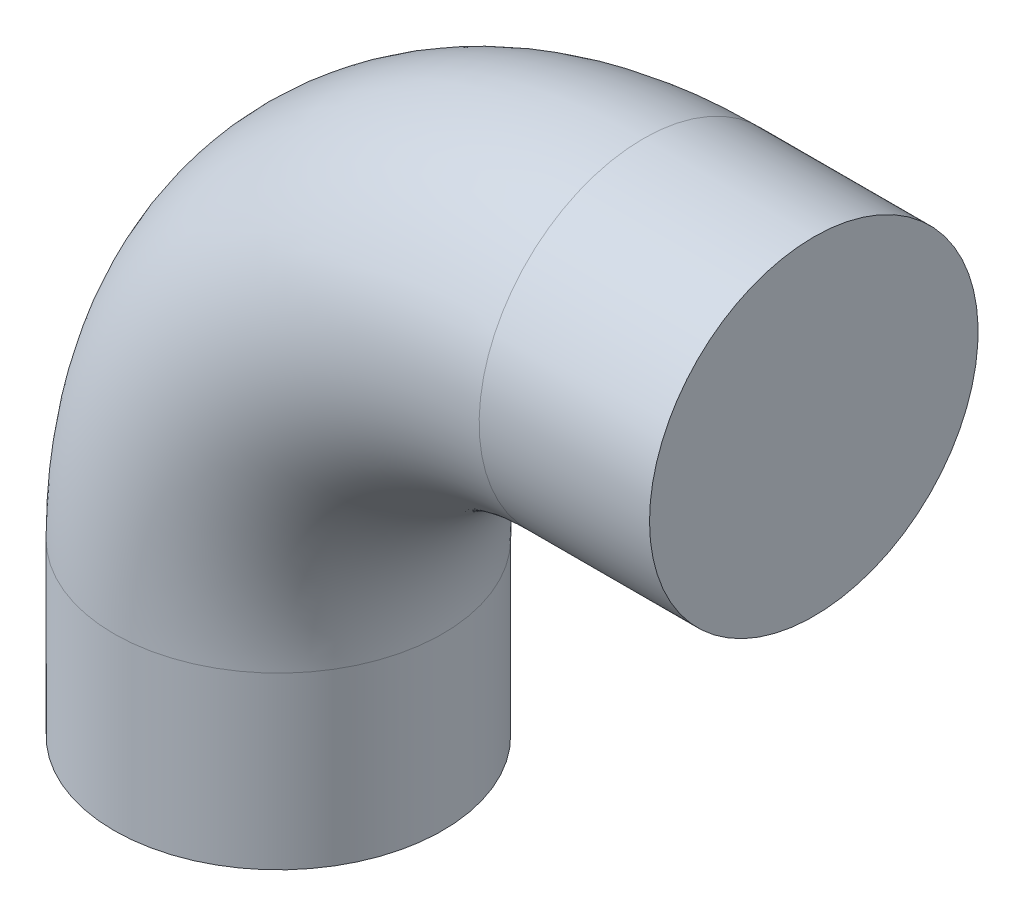
SolidWorks part; units mm, degrees
ref_plane "Front Plane" through (0, 0, 0) normal (0, 0, 1) x (1, 0, 0)
ref_plane "Top Plane" through (0, 0, 0) normal (0, 1, 0) x (1, 0, 0)
ref_plane "Right Plane" through (0, 0, 0) normal (1, 0, 0) x (0, 0, -1)
sketch "Sketch1" plane through (0, 0, 0) normal (0, 0, 1) x (1, 0, 0)
  line L0 (0, 0) -> (0, 7)
  line L1 (15, 22) -> (22, 22)
  arc A0 (0, 7) -> (15, 22) centre (15, 7) cw
  point P6 (0, 22)
  dimension "D3" = 15
  dimension "D1" = 22
  dimension "D2" = 22
  dimension "D4" = 90
sketch "Sketch2" plane through (0, 0, 0) normal (0, 1, 0) x (1, 0, 0)
  circle A0 centre (0, 0) radius 6.75
  dimension "D1" = 13.5
sweep "Sweep1" add profiles "Sketch2" path "Sketch1"
